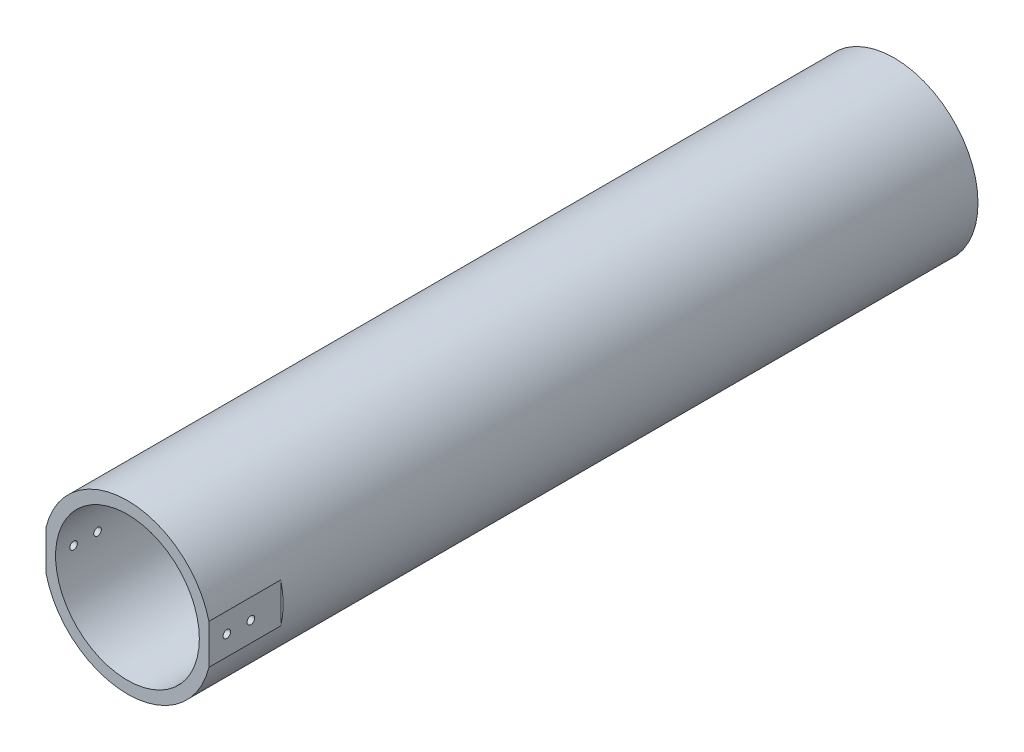
SolidWorks part; units mm, degrees
ref_plane "Front Plane" through (0, 0, 0) normal (0, 0, 1) x (1, 0, 0)
ref_plane "Top Plane" through (0, 0, 0) normal (0, 1, 0) x (1, 0, 0)
ref_plane "Right Plane" through (0, 0, 0) normal (1, 0, 0) x (0, 0, -1)
sketch "Sketch1" plane through (0, 0, 0) normal (0, 0, 1) x (1, 0, 0)
  circle A0 centre (0, 0) radius 38.1
  circle A1 centre (0, 0) radius 44.45
extrude "Boss-Extrude1" add sketch "Sketch1" along normal mid plane 406.4
sketch "Sketch2" plane through (0, 0, 203.2) normal (0, 0, 1) x (1, 0, 0)
  line L1 (43.18, 13.8246) -> (51.0798, 13.8246)
  line L2 (43.18, 13.8246) -> (43.18, -14.6378)
  line L3 (43.18, -14.6378) -> (51.0798, -14.6378)
  line L4 (51.0798, 13.8246) -> (51.0798, -14.6378)
  dimension "D1" = 43.18
extrude "Cut-Extrude1" cut sketch "Sketch2" against normal blind 38.1
hole_wizard "#10-32 Tapped Hole1" positions "Sketch4" profile "Sketch3" tap size "#10-32" standard "ANSI Inch"
sketch "Sketch4" plane through (43.18, 0, 0) normal (1, 0, 0) x (0, 0, -1)
  line L0 (-203.2, 10.5494) -> (-203.2, -10.5494) construction
  point P0 (-193.675, 0)
  point P2 (-180.975, 0)
  dimension "D1" = 9.525
  dimension "D2" = 12.7
sketch "Sketch3" plane through (43.18, 0, 193.675) normal (0, 1, 0) x (0, 0, -1)
  line L0 (0, 0) -> (0, 14.9293)
  line L1 (0, 14.9293) -> (2.0193, 13.716)
  line L2 (2.0193, 13.716) -> (2.0193, 0)
  line L5 (2.0193, 0) -> (0, 0)
  line L10 (0, 14.9293) -> (-2.0193, 13.716) construction
  line L11 (0, -6.35) -> (0, 107.95) construction
  dimension "Tap Drill Dia." = 4.0386
  dimension "Tap Drill Depth" = 13.716
  dimension "Drill Angle" = 118
cosmetic thread "Hole Thread1" parameters "D1"=5.1335, "D2"=4.826
cosmetic thread "Hole Thread2" parameters "D1"=5.1335, "D2"=4.826
hole_wizard "#8-32 Tapped Hole1" positions "Sketch6" profile "Sketch5" tap size "#8-32" standard "ANSI Inch"
sketch "Sketch6" plane through (0, 0, -203.2) normal (0, 0, -1) x (-1, 0, 0)
  point P0 (0, 41.275)
  point P2 (-41.275, 0)
  point P4 (41.275, 0)
  point P6 (0, -41.275)
  dimension "D1" = 41.275
  dimension "D2" = 41.275
  dimension "D3" = 41.275
  dimension "D4" = 41.275
sketch "Sketch5" plane through (0, 41.275, -203.2) normal (1, 0, 0) x (0, 1, 0)
  line L0 (0, 0) -> (0, 16.0238)
  line L1 (0, 16.0238) -> (1.7272, 14.986)
  line L2 (1.7272, 14.986) -> (1.7272, 0)
  line L5 (1.7272, 0) -> (0, 0)
  line L10 (0, 16.0238) -> (-1.7272, 14.986) construction
  line L11 (0, -6.35) -> (0, 107.95) construction
  dimension "Tap Drill Dia." = 3.4544
  dimension "Tap Drill Depth" = 14.986
  dimension "Drill Angle" = 118
cosmetic thread "Hole Thread3" parameters "D1"=10.922, "D2"=4.1656
cosmetic thread "Hole Thread4" parameters "D1"=10.922, "D2"=4.1656
cosmetic thread "Hole Thread5" parameters "D1"=10.922, "D2"=4.1656
cosmetic thread "Hole Thread6" parameters "D1"=10.922, "D2"=4.1656
mirror "Mirror1" about plane through (0, 0, 0) normal (1, 0, 0) of "#10-32 Tapped Hole1", "Cut-Extrude1"
